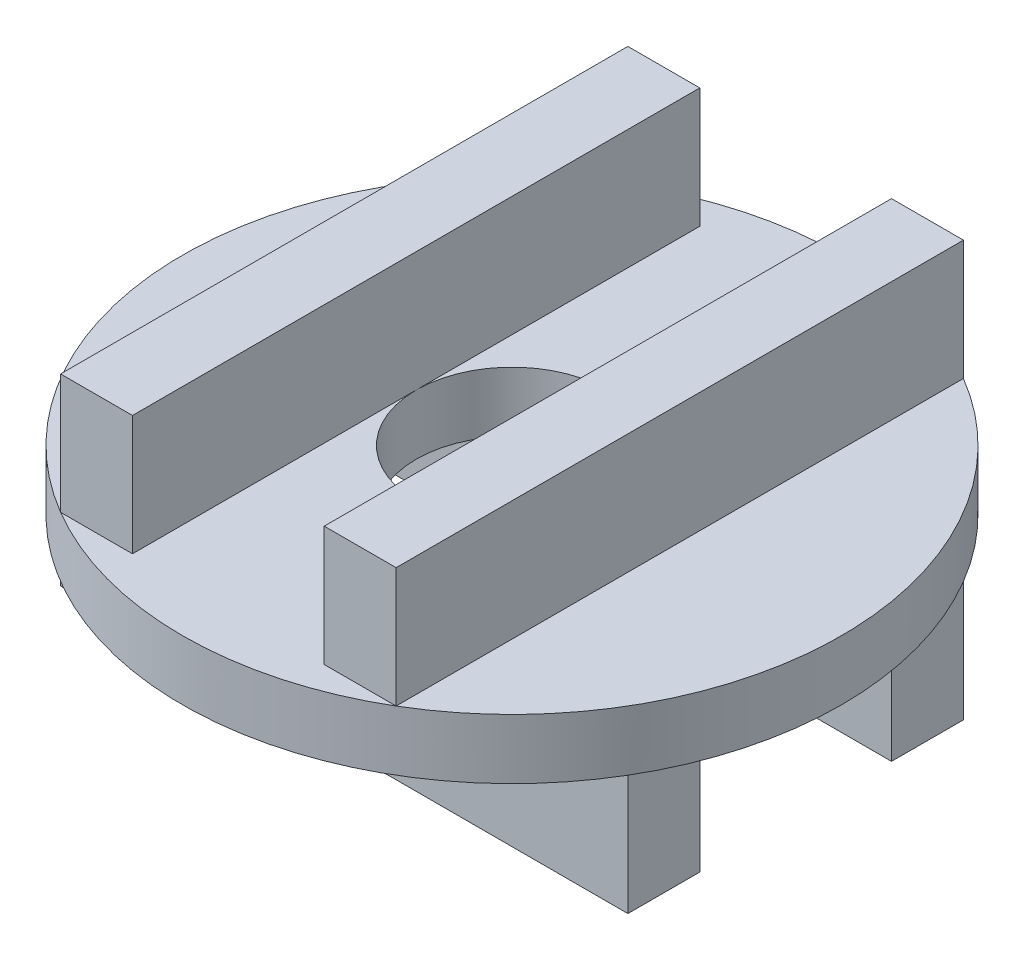
SolidWorks part; units mm, degrees
ref_plane "Front Plane" through (0, 0, 0) normal (0, 0, 1) x (1, 0, 0)
ref_plane "Top Plane" through (0, 0, 0) normal (0, 1, 0) x (1, 0, 0)
ref_plane "Right Plane" through (0, 0, 0) normal (1, 0, 0) x (0, 0, -1)
sketch "Sketch1" plane through (0, 0, 0) normal (0, 1, 0) x (1, 0, 0)
  circle A0 centre (0, 0) radius 55
  circle A1 centre (0, 0) radius 16
  point P5 (-1.3245, 0)
  dimension "D1" = 110
  dimension "D2" = 32
extrude "Boss-Extrude1" add sketch "Sketch1" along normal blind 10
sketch "Sketch2" plane through (0, 10, 0) normal (0, 1, 0) x (1, 0, 0)
  line L0 (0, 0) -> (0, 67.7196) construction
  line L1 (16, 47.3392) -> (28, 47.3392)
  line L2 (16, 47.3392) -> (16, -47.3392)
  line L3 (16, -47.3392) -> (28, -47.3392)
  line L4 (28, 47.3392) -> (28, -47.3392)
  line L5 (-28, 47.3392) -> (-28, -47.3392)
  line L6 (-16, -47.3392) -> (-28, -47.3392)
  line L7 (-16, 47.3392) -> (-16, -47.3392)
  line L8 (-16, 47.3392) -> (-28, 47.3392)
  circle A0 centre (0, 0) radius 55 construction
  circle A1 centre (0, 0) radius 16 construction
  point P4 (0, 67.7196)
  dimension "D1" = 12
extrude "Boss-Extrude2" add sketch "Sketch2" along normal blind 20
sketch "Sketch3" plane through (0, 0, 0) normal (0, -1, 0) x (1, 0, 0)
  line L0 (0, 0) -> (108.8111, 0) construction
  line L1 (-47.3392, 16) -> (47.3392, 16)
  line L2 (-47.3392, 16) -> (-47.3392, 28)
  line L3 (-47.3392, 28) -> (47.3392, 28)
  line L4 (47.3392, 16) -> (47.3392, 28)
  line L5 (47.3392, -16) -> (47.3392, -28)
  line L6 (-47.3392, -28) -> (47.3392, -28)
  line L7 (-47.3392, -16) -> (-47.3392, -28)
  line L8 (-47.3392, -16) -> (47.3392, -16)
  circle A0 centre (0, 0) radius 55 construction
  circle A1 centre (0, 0) radius 16 construction
  dimension "D1" = 12
extrude "Boss-Extrude3" add sketch "Sketch3" along normal blind 20
